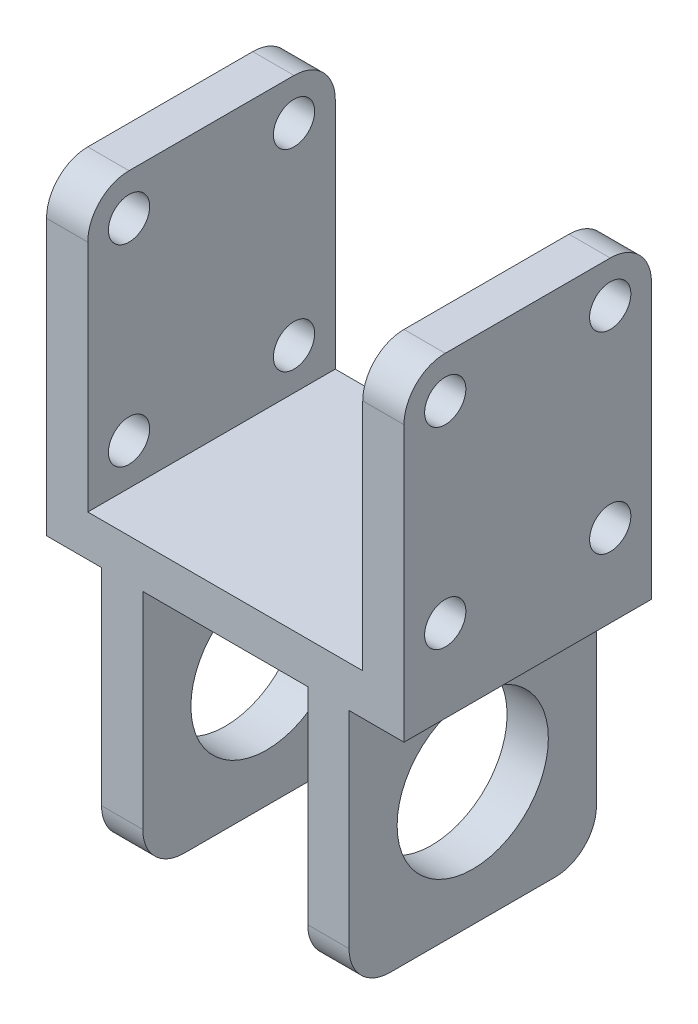
SolidWorks part; units mm, degrees
material "6061 合金"
ref_plane "前视基准面" through (0, 0, 0) normal (0, 0, 1) x (1, 0, 0)
ref_plane "上视基准面" through (0, 0, 0) normal (0, 1, 0) x (1, 0, 0)
ref_plane "右视基准面" through (0, 0, 0) normal (1, 0, 0) x (0, 0, -1)
sketch "草图1" plane through (0, 0, 0) normal (0, 1, 0) x (1, 0, 0)
  line L1 (-13, -9) -> (13, -9)
  line L2 (-13, -9) -> (-13, 9)
  line L3 (-13, 9) -> (13, 9)
  line L4 (13, -9) -> (13, 9)
  line L5 (-13, -9) -> (13, 9) construction
  line L6 (-13, 9) -> (13, -9) construction
  point P0 (0, 0)
  dimension "D1" = 18
  dimension "D2" = 26
extrude "凸台-拉伸1" add sketch "草图1" along normal blind 3
sketch "草图2" plane through (0, 3, 0) normal (0, 1, 0) x (1, 0, 0)
  line L0 (-13, -9) -> (13, -9) construction
  line L1 (-13, 9) -> (-10, 9)
  line L2 (-13, 9) -> (-13, -9)
  line L3 (-13, -9) -> (-10, -9)
  line L4 (-10, 9) -> (-10, -9)
  line L6 (13, 9) -> (10, 9)
  line L7 (13, 9) -> (13, -9)
  line L8 (13, -9) -> (10, -9)
  line L9 (10, 9) -> (10, -9)
  dimension "D1" = 3
  dimension "D2" = 3
extrude "凸台-拉伸2" add sketch "草图2" along normal blind 20
sketch "草图3" plane through (0, 0, 0) normal (0, -1, 0) x (1, 0, 0)
  line L0 (13, -9) -> (-13, -9) construction
  line L1 (-9, 9) -> (-6, 9)
  line L2 (-9, 9) -> (-9, -9)
  line L3 (-9, -9) -> (-6, -9)
  line L4 (-6, 9) -> (-6, -9)
  line L5 (-13, -9) -> (-13, 9) construction
  line L6 (9, 9) -> (6, 9)
  line L7 (9, 9) -> (9, -9)
  line L8 (9, -9) -> (6, -9)
  line L9 (6, 9) -> (6, -9)
  line L10 (13, 9) -> (13, -9) construction
  dimension "D1" = 3
  dimension "D2" = 3
  dimension "D3" = 4
  dimension "D4" = 4
extrude "凸台-拉伸3" add sketch "草图3" along normal blind 18
sketch "草图4" plane through (-13, 0, 0) normal (-1, 0, 0) x (0, 0, 1)
  line L0 (9, 3) -> (-9, 3) construction
  line L1 (0, 23) -> (0, 3) construction
  line L2 (-9, 23) -> (9, 23) construction
  line L3 (-9, 13) -> (9, 13) construction
  line L4 (-9, 23) -> (-9, 0) construction
  line L5 (9, 23) -> (9, 0) construction
  line L7 (-6, 6) -> (6, 6) construction
  line L8 (-6, 6) -> (-6, 20) construction
  line L9 (-6, 20) -> (6, 20) construction
  line L10 (6, 6) -> (6, 20) construction
  line L11 (-6, 6) -> (6, 20) construction
  line L12 (-6, 20) -> (6, 6) construction
  circle A0 centre (-6, 20) radius 1.5
  circle A1 centre (6, 20) radius 1.5
  circle A2 centre (6, 6) radius 1.5
  circle A3 centre (-6, 6) radius 1.5
  point P12 (0, 13)
  dimension "D3" = 3
  dimension "D1" = 12
  dimension "D2" = 14
extrude "切除-拉伸1" cut sketch "草图4" against normal through all
fillet "圆角1" radius 3 4 edges at (11.5, 23, 9) (11.5, 23, -9) (-11.5, 23, -9) (-11.5, 23, 9)
sketch "草图5" plane through (-13, 0, 0) normal (-1, 0, 0) x (0, 0, 1)
  line L0 (0, 0) -> (0, -18) construction
  line L1 (9, -18) -> (-9, -18) construction
  line L2 (-9, -8) -> (9, -8) construction
  line L3 (-9, 20) -> (-9, 0) construction
  line L4 (9, 20) -> (9, 0) construction
  line L5 (-9, 0) -> (9, 0) construction
  circle A0 centre (0, -9) radius 5.5
  dimension "D2" = 11
  dimension "D1" = 8
extrude "切除-拉伸2" cut sketch "草图5" against normal through all
fillet "圆角2" radius 3 4 edges at (7.5, -18, 9) (-7.5, -18, 9) (-7.5, -18, -9) (7.5, -18, -9)
